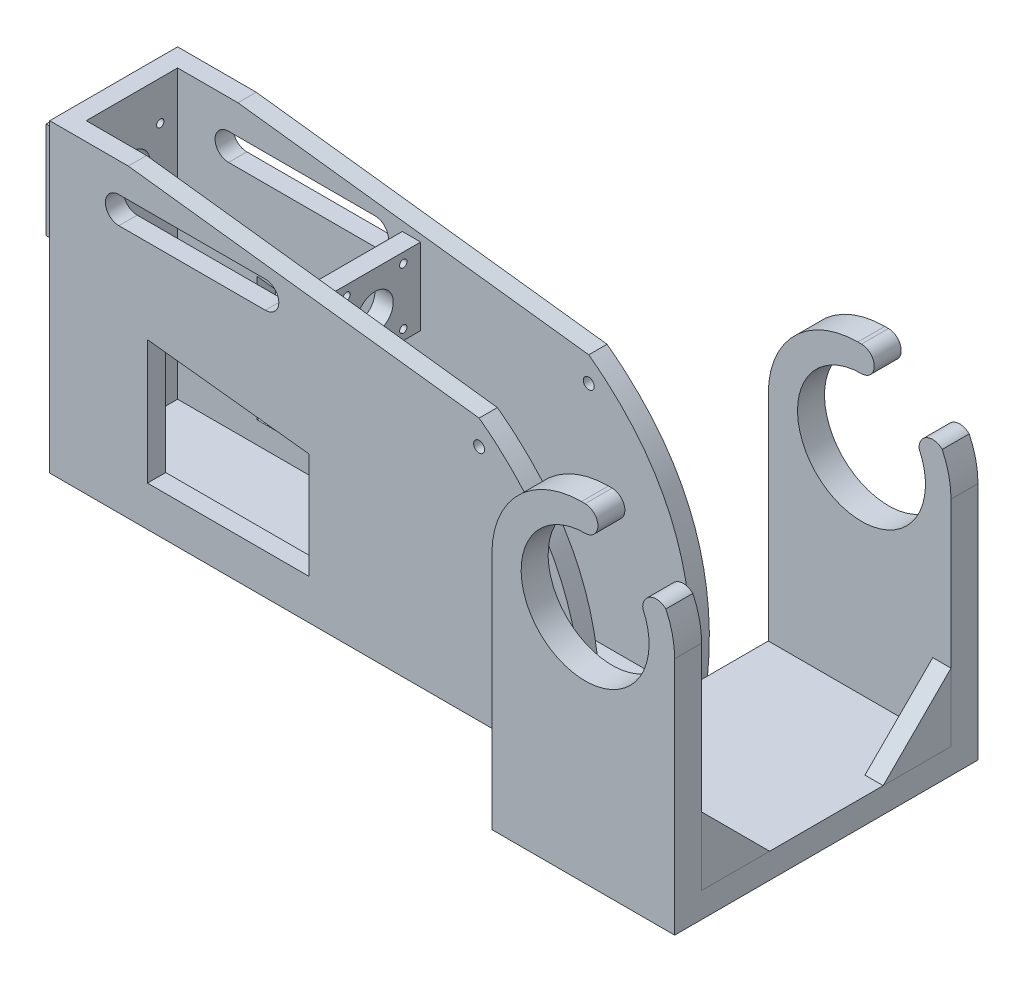
SolidWorks part; units mm, degrees
ref_plane "Alzado" through (0, 0, 0) normal (0, 0, 1) x (1, 0, 0)
ref_plane "Planta" through (0, 0, 0) normal (0, 1, 0) x (1, 0, 0)
ref_plane "Vista lateral" through (0, 0, 0) normal (1, 0, 0) x (0, 0, -1)
sketch "Croquis1" plane through (0, 0, 0) normal (0, 0, 1) x (1, 0, 0)
  line L1 (50, -90) -> (-50, -90)
  line L2 (50, -90) -> (50, 41)
  line L3 (1, 90) -> (-1, 90)
  line L4 (-50, -90) -> (-50, 41)
  line L5 (50, -90) -> (-50, 90) construction
  line L6 (50, 90) -> (-50, -90) construction
  arc A0 (50, 41) -> (1, 90) centre (1, 41) ccw
  arc A1 (-1, 90) -> (-50, 41) centre (-1, 41) ccw
  circle A2 centre (1, 41) radius 35
  arc A3 (1, 76) -> (1, 90) centre (1, 83) ccw
  arc A4 (32.5628, 56.1257) -> (45.188, 62.176) centre (39.9822, 56.8413) cw
  point P0 (0, 0)
  dimension "D3" = 49
  dimension "D1" = 180
  dimension "D2" = 100
extrude "Saliente-Extruir1" add sketch "Croquis1" along normal blind 166 contours A4 A2 A3 L3 A1 L4 L1 L2 A0
sketch "Croquis2" plane through (50, 0, 0) normal (1, 0, 0) x (0, 0, -1)
  line L0 (-166, 90) -> (0, 90) construction
  line L1 (-151.2362, 256.1971) -> (-14.7638, 256.1971)
  line L2 (-151.2362, 256.1971) -> (-151.2362, -76.1971)
  line L3 (-151.2362, -76.1971) -> (-14.7638, -76.1971)
  line L4 (-14.7638, 256.1971) -> (-14.7638, -76.1971)
  line L5 (-151.2362, 256.1971) -> (-14.7638, -76.1971) construction
  line L6 (-151.2362, -76.1971) -> (-14.7638, 256.1971) construction
  point P0 (-83, 90)
extrude "Cortar-Extruir1" cut sketch "Croquis2" against normal through all
ref_plane "Plano1" through (0, 0, 83) normal (0, 0, -1) x (-1, 0, 0)
ref_plane "Plano2" through (0, 0, 118) normal (0, 0, -1) x (-1, 0, 0)
sketch "Croquis3" plane through (0, 0, 118) normal (0, 0, -1) x (-1, 0, 0)
  line L0 (297, 77) -> (105, 53.5493)
  line L1 (50, -90) -> (340, -90)
  line L2 (50, -90) -> (50, 35) construction
  line L3 (50, 35) -> (340, 35) construction
  line L4 (340, -90) -> (340, 35)
  line L5 (340, -90) -> (297, -90)
  line L6 (340, -90) -> (340, 77)
  line L7 (340, 77) -> (297, 77)
  line L8 (297, -90) -> (297, 77) construction
  line L9 (50, -90) -> (105, -90) construction
  line L10 (50, -90) -> (50, 40) construction
  line L11 (50, 40) -> (105, 40) construction
  line L12 (105, -90) -> (105, 40) construction
  line L13 (50, -76.1971) -> (50, -90)
  line L14 (222, 53.5493) -> (302.1218, 53.5493) construction
  line L15 (222, 60.9289) -> (302.1218, 60.9289)
  line L16 (222, 46.1696) -> (302.1218, 46.1696)
  line L17 (198, -10) -> (286.5, 0)
  line L18 (286.5, -68) -> (198, -68)
  line L19 (286.5, -68) -> (286.5, -10)
  line L20 (286.5, -10) -> (198, -10) construction
  line L21 (198, -68) -> (198, -10)
  line L22 (286.5, 0) -> (286.5, -10)
  circle A0 centre (105, 40) radius 3
  arc A1 (222, 60.9289) -> (222, 46.1696) centre (222, 53.5493) ccw
  arc A2 (302.1218, 46.1696) -> (302.1218, 60.9289) centre (302.1218, 53.5493) ccw
  spline S0 degree 2 poles (50, -76.1971) (41.5656, 6.5835) (105, 53.5493) knots 0 0 0 1 1 1
  point P18 (262.0609, 53.5493)
  dimension "D7" = 6
  dimension "D1" = 290
  dimension "D2" = 125
  dimension "D3" = 167
  dimension "D4" = 43
  dimension "D5" = 130
  dimension "D6" = 55
  dimension "D8" = 142
  dimension "D9" = 22
  dimension "D10" = 53.5
  dimension "D11" = 58
  dimension "D12" = 68
  dimension "D13" = 118
extrude "Saliente-Extruir2" add sketch "Croquis3" along normal blind 10 contours S0 L13 L1 L4 L6 L7 L0 A2 L16 A1 L15 A0 L17 L22 L19 L18 L21
mirror "Simetría1" about plane through (0, 0, 83) normal (0, 0, -1) of "Saliente-Extruir2"
sketch "Croquis4" plane through (0, -90, 0) normal (0, -1, 0) x (1, 0, 0)
  line L1 (-340, 118) -> (-50, 118)
  line L2 (-340, 118) -> (-340, 48)
  line L3 (-340, 48) -> (-50, 48)
  line L4 (-50, 118) -> (-50, 48)
extrude "Saliente-Extruir4" add sketch "Croquis4" against normal blind 10
sketch "Croquis5" plane through (-340, 0, 0) normal (-1, 0, 0) x (0, 0, 1)
  line L1 (48, -90) -> (118, -90)
  line L2 (48, -90) -> (48, 77)
  line L3 (48, 77) -> (118, 77)
  line L4 (118, -90) -> (118, 77)
extrude "Saliente-Extruir5" add sketch "Croquis5" against normal blind 10
sketch "Croquis6" plane through (50, 0, 0) normal (1, 0, 0) x (0, 0, -1)
  line L0 (-151.2362, -76.1971) -> (-114.0168, -76.1971)
  line L1 (-151.2362, -76.1971) -> (-14.7638, -76.1971) construction
  line L2 (-114.0168, -76.1971) -> (-151.2362, -38.9777)
  line L3 (-151.2362, 41) -> (-151.2362, -76.1971) construction
  line L4 (-151.2362, -38.9777) -> (-151.2362, -76.1971)
  line L5 (-14.7638, -76.1971) -> (-51.8836, -76.1971)
  line L6 (-51.8836, -76.1971) -> (-14.7638, -39.0773)
  line L7 (-14.7638, -76.1971) -> (-14.7638, 41) construction
  line L8 (-14.7638, -39.0773) -> (-14.7638, -76.1971)
extrude "Saliente-Extruir6" add sketch "Croquis6" against normal blind 10 separate body
ref_plane "Plano3" through (-197, 0, 0) normal (-1, 0, 0) x (0, 0, 1)
sketch "Croquis7" plane through (-197, 0, 0) normal (-1, 0, 0) x (0, 0, 1)
  line L0 (83, 55) -> (83, -55) construction
  line L1 (108, 19) -> (58, 19)
  line L2 (108, 19) -> (108, 61)
  line L3 (108, 61) -> (58, 61)
  line L4 (58, 19) -> (58, 61)
  line L5 (108, 19) -> (58, 61) construction
  line L6 (108, 61) -> (58, 19) construction
  line L7 (58, -76.1971) -> (58, 53.5493) construction
  line L8 (166, -90) -> (0, -90) construction
  line L10 (98.5, 24.5) -> (67.5, 24.5) construction
  line L11 (98.5, 24.5) -> (98.5, 55.5) construction
  line L12 (98.5, 55.5) -> (67.5, 55.5) construction
  line L13 (67.5, 24.5) -> (67.5, 55.5) construction
  line L14 (98.5, 24.5) -> (67.5, 55.5) construction
  line L15 (98.5, 55.5) -> (67.5, 24.5) construction
  circle A0 centre (83, 40) radius 10
  circle A1 centre (67.5, 55.5) radius 2.0281
  circle A2 centre (98.5, 55.5) radius 1.9891
  circle A3 centre (98.5, 24.5) radius 1.9965
  circle A4 centre (67.5, 24.5) radius 1.9895
  point P0 (83, 40)
  dimension "D3" = 20
  dimension "D1" = 42
  dimension "D2" = 130
  dimension "D4" = 31
  dimension "D5" = 31
extrude "Saliente-Extruir7" add sketch "Croquis7" along normal blind 10
sketch "Croquis8" plane through (-330, 0, 0) normal (1, 0, 0) x (0, 0, -1)
  circle A0 centre (-98.5, 24.5) radius 1.9965 construction
  circle A1 centre (-67.5, 24.5) radius 1.9895 construction
  circle A2 centre (-67.5, 55.5) radius 2.0281 construction
  circle A3 centre (-98.5, 55.5) radius 1.9891 construction
  circle A4 centre (-83, 40) radius 10 construction
  circle A5 centre (-98.5, 24.5) radius 1.9965
  circle A6 centre (-67.5, 24.5) radius 1.9895
  circle A7 centre (-67.5, 55.5) radius 2.0281
  circle A8 centre (-98.5, 55.5) radius 1.9891
  circle A9 centre (-83, 40) radius 10
extrude "Cortar-Extruir2" cut sketch "Croquis8" against normal through all
sketch "Croquis9" plane through (-340, 0, 0) normal (-1, 0, 0) x (0, 0, 1)
  line L1 (110.0174, 13.5554) -> (55.9826, 13.5554)
  line L2 (110.0174, 13.5554) -> (110.0174, 66.4446)
  line L3 (110.0174, 66.4446) -> (55.9826, 66.4446)
  line L4 (118, 77) -> (48, 77)
  line L5 (48, 77) -> (48, -90)
  line L6 (48, -90) -> (118, -90)
  line L7 (118, -90) -> (118, 77)
  line L8 (118, 77) -> (48, 77)
  line L9 (48, 77) -> (48, -90)
  line L10 (48, -90) -> (118, -90)
  line L11 (118, -90) -> (118, 77)
  line L12 (55.9826, 13.5554) -> (55.9826, 66.4446)
  line L13 (110.0174, 13.5554) -> (55.9826, 66.4446) construction
  line L14 (110.0174, 66.4446) -> (55.9826, 13.5554) construction
  point P2 (83, 40)
  circle M5 centre (67.5, 24.5) radius 1.9895
  circle M6 centre (67.5, 55.5) radius 2.0281
  circle M7 centre (98.5, 55.5) radius 1.9891
  circle M8 centre (83, 40) radius 10
  circle M9 centre (98.5, 24.5) radius 1.9965
  dimension "D1" = 0
extrude "Saliente-Extruir8" add sketch "Croquis9" along normal blind 10 contours L12 L1 L2 L3 M6 M8 M9 M7 M5
